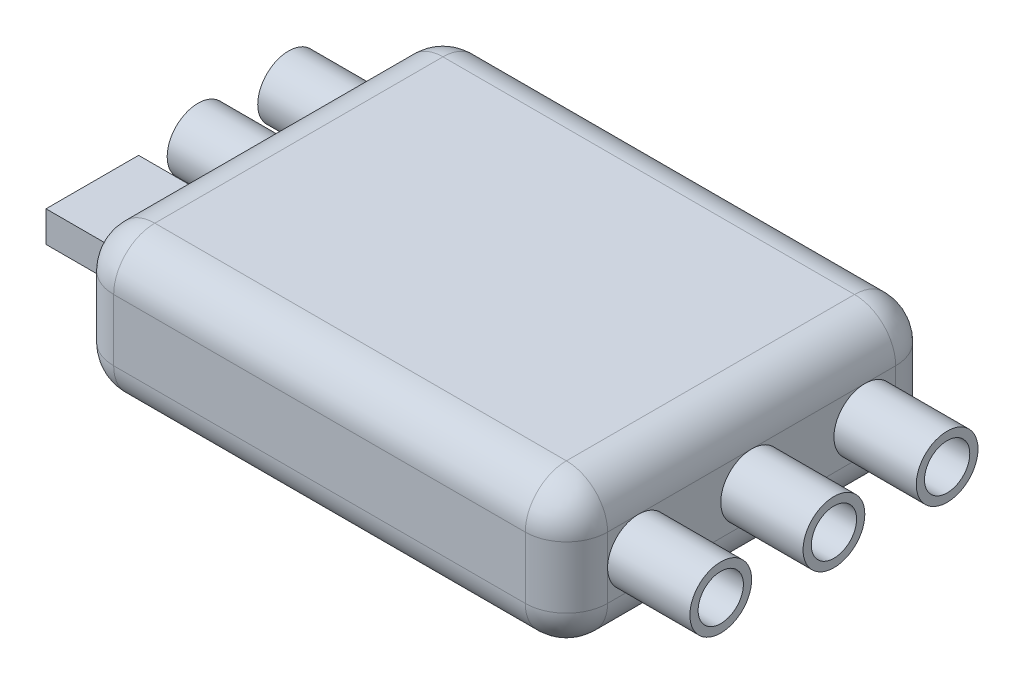
SolidWorks part; units mm, degrees
ref_plane "Front Plane" through (0, 0, 0) normal (0, 0, 1) x (1, 0, 0)
ref_plane "Top Plane" through (0, 0, 0) normal (0, 1, 0) x (1, 0, 0)
ref_plane "Right Plane" through (0, 0, 0) normal (1, 0, 0) x (0, 0, -1)
sketch "Sketch1" plane through (0, 0, 0) normal (0, 1, 0) x (1, 0, 0)
  line L1 (10, 9) -> (-10, 9)
  line L2 (12, 7) -> (12, -7)
  line L3 (10, -9) -> (-10, -9)
  line L4 (-12, 7) -> (-12, -7)
  line L5 (12, 9) -> (-12, -9) construction
  line L6 (12, -9) -> (-12, 9) construction
  arc A0 (-10, 9) -> (-12, 7) centre (-10, 7) ccw
  arc A1 (12, -7) -> (10, -9) centre (10, -7) cw
  arc A2 (10, 9) -> (12, 7) centre (10, 7) cw
  arc A3 (-10, -9) -> (-12, -7) centre (-10, -7) cw
  point P0 (0, 0)
  dimension "D3" = 2
  dimension "D1" = 24
  dimension "D2" = 18
extrude "Boss-Extrude1" add sketch "Sketch1" along normal blind 7
fillet "Fillet1" radius 2 16 edges at (11.4142, 0, 8.4142) (0, 0, 9) (-11.4142, 0, 8.4142) (-12, 0, 0) (-11.4142, 0, -8.4142) (0, 0, -9) (11.4142, 0, -8.4142) (12, 0, 0) (0, 7, -9) (11.4142, 7, -8.4142) (12, 7, 0) (11.4142, 7, 8.4142) (0, 7, 9) (-11.4142, 7, 8.4142) (-12, 7, 0) (-11.4142, 7, -8.4142)
sketch "Sketch2" plane through (12, 0, 0) normal (1, 0, 0) x (0, 0, -1)
  line L0 (-7, 3.5) -> (7, 3.5) construction
  line L1 (-7, 5) -> (-7, 2) construction
  line L2 (7, 5) -> (7, 2) construction
  circle A0 centre (0, 3.5) radius 1.5
  circle A1 centre (0, 3.5) radius 1.1
  circle A2 centre (-5.5, 3.5) radius 1.5
  circle A3 centre (5.5, 3.5) radius 1.5
  circle A4 centre (5.5, 3.5) radius 1.1
  circle A5 centre (-5.5, 3.5) radius 1.1
  dimension "D1" = 3
  dimension "D2" = 0.4
  dimension "D4" = 3
extrude "Boss-Extrude2" add sketch "Sketch2" along normal blind 4
sketch "Sketch3" plane through (-12, 0, 0) normal (-1, 0, 0) x (0, 0, 1)
  line L0 (-7, 3.5) -> (7, 3.5) construction
  line L1 (-7, 5) -> (-7, 2) construction
  line L2 (7, 5) -> (7, 2) construction
  line L4 (6.2881, 4.25) -> (1.7881, 4.25)
  line L5 (6.2881, 4.25) -> (6.2881, 2.75)
  line L6 (6.2881, 2.75) -> (1.7881, 2.75)
  line L7 (1.7881, 4.25) -> (1.7881, 2.75)
  circle A0 centre (-5.5, 3.5) radius 1.5
  circle A1 centre (-1.1, 3.5) radius 1.5
  circle A2 centre (-1.1, 3.5) radius 1.1
  circle A3 centre (-5.5, 3.5) radius 1.1
  dimension "D3" = 3
  dimension "D4" = 0.4
  dimension "D5" = 4.4
  dimension "D1" = 4.5
  dimension "D2" = 1.5
extrude "Boss-Extrude3" add sketch "Sketch3" along normal blind 4
